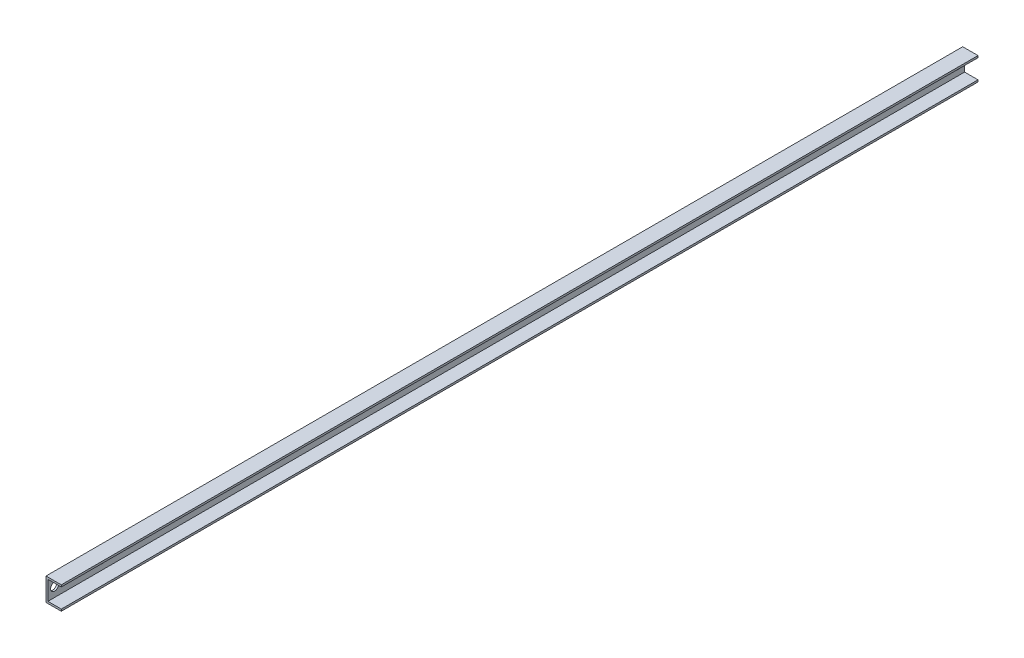
SolidWorks part; units mm, degrees
ref_plane "Front Plane" through (0, 0, 0) normal (0, 0, 1) x (1, 0, 0)
ref_plane "Top Plane" through (0, 0, 0) normal (0, 1, 0) x (1, 0, 0)
ref_plane "Right Plane" through (0, 0, 0) normal (1, 0, 0) x (0, 0, -1)
sketch "Sketch1" plane through (0, 0, 0) normal (0, 0, 1) x (1, 0, 0)
  line L0 (0, 0) -> (12.7, 0)
  line L1 (12.7, 0) -> (12.7, 1.5875)
  line L2 (12.7, 1.5875) -> (1.5875, 1.5875)
  line L3 (0, 19.05) -> (12.7, 19.05)
  line L5 (0, 19.05) -> (0, 0)
  line L6 (12.7, 19.05) -> (12.7, 17.4625)
  line L7 (12.7, 17.4625) -> (1.5875, 17.4625)
  line L8 (1.5875, 17.4625) -> (1.5875, 1.5875)
  dimension "D1" = 19.05
  dimension "D2" = 12.7
  dimension "D3" = 1.5875
  dimension "D4" = 1.5875
extrude "Boss-Extrude1" add sketch "Sketch1" along normal blind 762
hole_wizard "17/64 (0.26563) Diameter Hole1" positions "3DSketch1" profile "Sketch2" hole size "17/64" standard "Ansi Inch" end condition through all
sketch3d "3DSketch1"
  line L5 (0, 19.05, 0) -> (0, 0, 0) construction
  line L7 (0, 9.525, 0) -> (0, 9.525, 762) construction
  line L9 (0, 0, 762) -> (0, 0, 0) construction
  line L10 (0, 19.05, 762) -> (0, 0, 762) construction
  line L11 (0, 9.525, 381) -> (0, -61.5173, 381) construction
  point P39 (0, 9.525, 5.588)
  point P42 (0, 9.525, 45.212)
  point P48 (0, 9.525, 716.787)
  point P50 (0, 9.525, 756.412)
  dimension "D1" = 9.525
  dimension "D3" = 39.624
  dimension "D2" = 375.412
  dimension "D4" = 39.625
  dimension "D5" = 750.824
sketch "Sketch2" plane through (0, 9.525, 5.588) normal (0, 1, 0) x (0, 0, 1)
  line L0 (0, 0) -> (0, 12.7)
  line L1 (0, 12.7) -> (3.3735, 12.7)
  line L2 (3.3735, 12.7) -> (3.3735, 0)
  line L5 (3.3735, 0) -> (0, 0)
  line L11 (0, -6.35) -> (0, 107.95) construction
  dimension "Thru Hole Dia." = 6.747
  dimension "Thru Hole Depth" = 12.7
equation "\"D2@3DSketch1\" = \"D5@3DSketch1\"/2"
